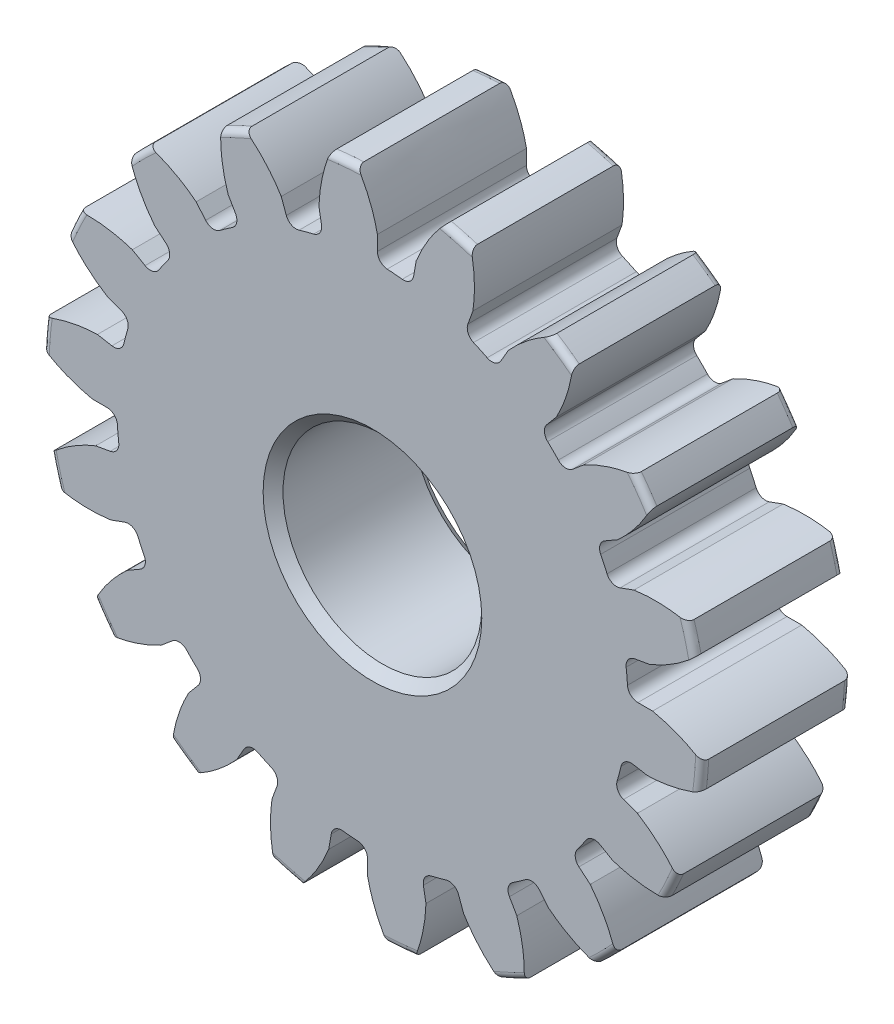
SolidWorks part; units mm, degrees
ref_plane "Front" through (0, 0, 0) normal (0, 0, 1) x (1, 0, 0)
ref_plane "Top" through (0, 0, 0) normal (0, 1, 0) x (1, 0, 0)
ref_plane "Right" through (0, 0, 0) normal (1, 0, 0) x (0, 0, -1)
sketch "Sketch1" plane through (0, 0, 0) normal (0, 0, 1) x (1, 0, 0)
  line L0 (-228.6, 0) -> (228.6, 0) construction
  circle A0 centre (0, 0) radius 10.541
  circle A1 centre (0, 0) radius 9.525 construction
  circle A3 centre (0, 0) radius 8.1598 construction
  dimension "D3" = 1.016
  dimension "D1" = 2.3813
extrude "Boss-Extrude1" add sketch "Sketch1" against normal blind 4.7625
sketch "Sketch2" plane through (0, 0, 0) normal (1, 0, 0) x (0, 0, -1)
  line L0 (4.7625, 0) -> (11.0998, 0)
  line L1 (4.7625, 0) -> (4.7625, 6.35)
  line L2 (4.7625, 6.35) -> (11.0998, 6.35)
  line L3 (11.0998, 6.35) -> (11.0998, 0)
  point P5 (11.0998, -6.35)
  point P6 (0, -10.541)
  point P7 (4.7625, -10.541)
  point P9 (0, 10.541)
revolve "Revolve1" add sketch "Sketch2" angle 360 mid plane about L0
fillet "Fillet2" radius 0.2108 3 edges at (10.541, 0, -4.7625) (10.541, 0, 0) (6.35, 0, -4.7625)
sketch "Sketch3" plane through (0, 0, 0) normal (0, 0, 1) x (1, 0, 0)
  line L0 (0, 0) -> (0, 10.541) construction
  line L1 (-3.0613, 8.4108) -> (0, 9.525)
  line L2 (-9.5921, 9.525) -> (9.5921, 9.525) construction
  line L3 (-9.0136, 6.2443) -> (9.0136, 12.8057) construction
  line L4 (-3.0613, 8.4108) -> (0, 0) construction
  line L5 (-7.3721, 5.0759) -> (0, 0) construction
  line L6 (-7.3721, 5.0759) -> (-2.3984, 12.2997) construction
  line L7 (-2.1265, 8.6943) -> (0, 0) construction
  line L8 (-2.1265, 8.6943) -> (0.0886, 9.2361) construction
  arc A0 (-3.0613, 8.4108) -> (-7.3721, 5.0759) centre (0, 0) ccw
  circle A1 centre (0, 0) radius 9.525 construction
  circle A2 centre (0, 0) radius 8.9506 construction
  arc A3 (-3.0613, 8.4108) -> (-2.1265, 8.6943) centre (0, 0) cw
  circle A4 centre (0, 0) radius 10.541 construction
  point P6 (0, 9.525)
  dimension "D1" = 3.2577
  dimension "Pressure Angle" = 20
  dimension "D2" = 5.5382
  dimension "D3" = 8.7705
  dimension "D4" = 0.9773
  dimension "D5" = 2.2804
sketch "Sketch4" plane through (0, 0, 0) normal (0, 0, 1) x (1, 0, 0)
  line L0 (0, 0) -> (0.827, 9.4526) construction
  line L1 (0.1576, 8.9492) -> (0.1576, 8.1582)
  line L2 (0, 9.525) -> (1.654, 9.3803) construction
  line L3 (1.3988, 8.8406) -> (1.2615, 8.0616)
  line L4 (0.1576, 8.1582) -> (0, 0) construction
  line L5 (0, 0) -> (0, 10.541) construction
  line L6 (-7.3721, 5.0759) -> (-2.3984, 12.2997) construction
  line L7 (-7.3721, 5.0759) -> (-2.3984, 12.2997) construction
  arc A0 (1.2615, 8.0616) -> (0.1576, 8.1582) centre (0, 0) ccw
  arc A1 (0, 9.525) -> (1.654, 9.3803) centre (0, 0) cw construction
  circle A2 centre (0, 0) radius 9.525 construction
  circle A3 centre (0, 0) radius 8.9506 construction
  circle A4 centre (0, 0) radius 8.1598 construction
  arc A5 (4.4978, 11.6964) -> (-2.3984, 12.2997) centre (0, 0) ccw
  spline S0 degree 2 poles (-2.3984, 12.2997) (-0.2792, 11.04) (0.1576, 8.9492) knots 0 0 0 1 1 1
  spline S1 degree 2 poles (4.4978, 11.6964) (2.1921, 10.8237) (1.3988, 8.8406) knots 0 0 0 1 1 1
  dimension "D1" = 1.6624
extrude "Cut-Extrude1" cut sketch "Sketch4" against normal through all
fillet "Fillet1" radius 0.3325 2 edges at (1.2615, 8.0616, -2.3813) (0.1576, 8.1582, -2.3813)
pattern_circular "CirPattern1" count 18 over 360 about axis through (0, 0, -4.7625) along (0, 0, 1) of "Cut-Extrude1", "Fillet1"
sketch "Sketch5" plane through (0, 0, 0) normal (0, 0, 1) x (1, 0, 0)
  line L0 (0, 4.3663) -> (0, 0) construction
  line L1 (-1.1906, 2.9433) -> (1.1906, 2.9433) construction
  line L2 (-1.1906, 2.9433) -> (-1.1906, 4.3663) construction
  line L3 (-1.1906, 4.3663) -> (1.1906, 4.3663) construction
  line L4 (1.1906, 2.9433) -> (1.1906, 4.3663) construction
  line L5 (-1.1906, 2.9433) -> (1.1906, 4.3663) construction
  line L6 (-1.1906, 4.3663) -> (1.1906, 2.9433) construction
  circle A0 centre (0, 0) radius 3.175
  point P3 (0, 3.6548)
  point P8 (0, 3.175)
  point P9 (0, -3.175)
  dimension "Bore Min" = 6.35
  dimension "Keyway Wd" = 2.3813
  dimension "Keyway Dpt." = 1.1913
extrude "Cut-Extrude2" cut sketch "Sketch5" against normal through all
sketch "Pitch Dia" plane through (0, 0, 0) normal (0, 0, 1) x (1, 0, 0)
  circle A0 centre (0, 0) radius 9.525 construction
  circle A1 centre (0, 0) radius 9.525 construction
sketch "Sketch6" plane through (0, 0, -4.7625) normal (0, 0, -1) x (-1, 0, 0)
  circle A0 centre (0, 0) radius 9.525
  dimension "D1" = 19.05
extrude "Cut-Extrude3" cut sketch "Sketch6" along normal through all
chamfer "Chamfer1" distance 0.3175 angle 45 2 edges at (3.175, 0, 0) (-3.175, 0, -4.7625)
equation "\"D1@Boss-Extrude1\" = \"Face Wd@Sketch2\""
equation "\"D1@Sketch4\" = 1.5708/(\"Number of Teeth@Sketch1\"/\"Ptich Dia@Sketch1\")"
equation "\"D1@Chamfer1\" = \"B Hub Dia@Sketch2\"*.025"
equation "\"D1@CirPattern1\" = \"Number of Teeth@Sketch1\""
equation "\"D1@Fillet1\" = \"D1@Sketch4\"*.2"
equation "\"D1@Fillet2\" = \"OD@Sketch1\"*.01"
equation "\"D1@Sketch1\" = 2.250/(\"Number of Teeth@Sketch1\"/\"Ptich Dia@Sketch1\")"
